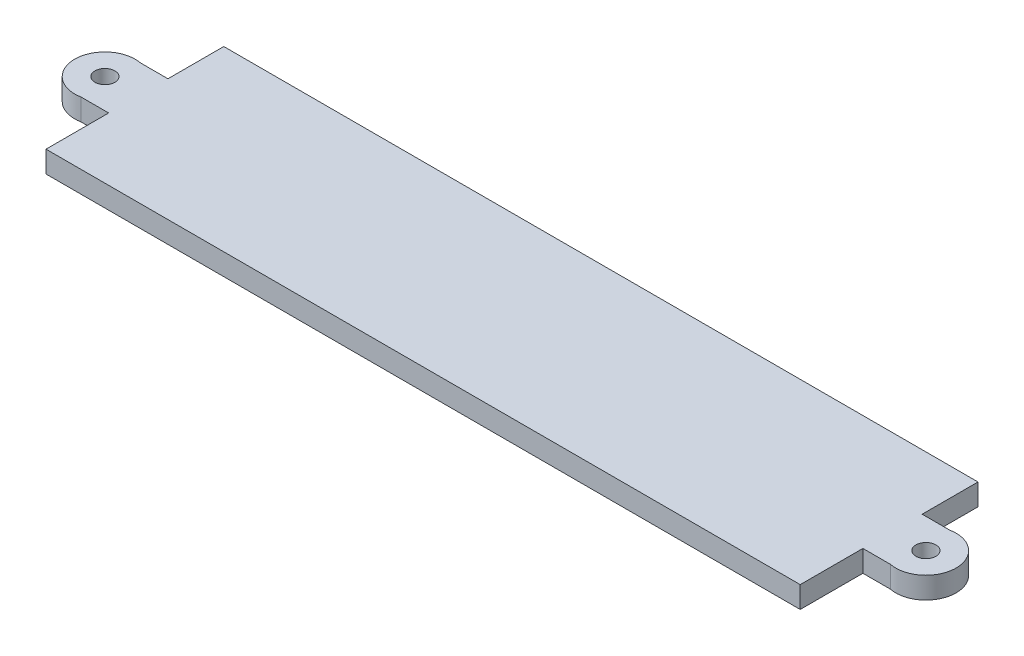
SolidWorks part; units mm, degrees
ref_plane "Front Plane" through (0, 0, 0) normal (0, 0, 1) x (1, 0, 0)
ref_plane "Top Plane" through (0, 0, 0) normal (0, 1, 0) x (1, 0, 0)
ref_plane "Right Plane" through (0, 0, 0) normal (1, 0, 0) x (0, 0, -1)
sketch "Sketch1" plane through (0, 0, 0) normal (0, 1, 0) x (1, 0, 0)
  line L0 (-70.9534, -29.866) -> (17.9466, -29.866)
  line L1 (-70.9534, -29.866) -> (-70.9534, 12.044)
  line L2 (17.9466, -29.866) -> (17.9466, 12.044)
  line L3 (-70.9534, 12.044) -> (17.9466, 12.044)
  line L5 (-70.9534, -1.1219) -> (-78.8274, -1.1219)
  line L6 (-70.9534, -1.1219) -> (-70.9534, -15.0919)
  line L7 (-70.9534, -15.0919) -> (-78.8274, -15.0919)
  line L8 (-78.8274, -1.1219) -> (-78.8274, -15.0919)
  circle A0 centre (-78.8274, -8.1069) radius 7.1211
  dimension "D1" = 88.9
  dimension "D2" = 41.91
  dimension "D3" = 13.97
  dimension "D4" = 7.874
extrude "Boss-Extrude1" add sketch "Sketch1" along normal blind 5.08 contours L5 A0 L7 L8 | L7 A0 L5 L8 | A0 L7 L1 L5 | L3 L1 L0 L2
sketch "Sketch2" plane through (0, 0, 0) normal (0, -1, 0) x (-1, 0, 0)
  circle A1 centre (78.8274, -8.1069) radius 2.3495
  dimension "D1" = 4.699
extrude "Cut-Extrude1" cut sketch "Sketch2" against normal up to next
mirror "Mirror2" about plane through (17.9466, 5.08, 0) normal (-1, 0, 0) of "Boss-Extrude1", "Cut-Extrude1"
